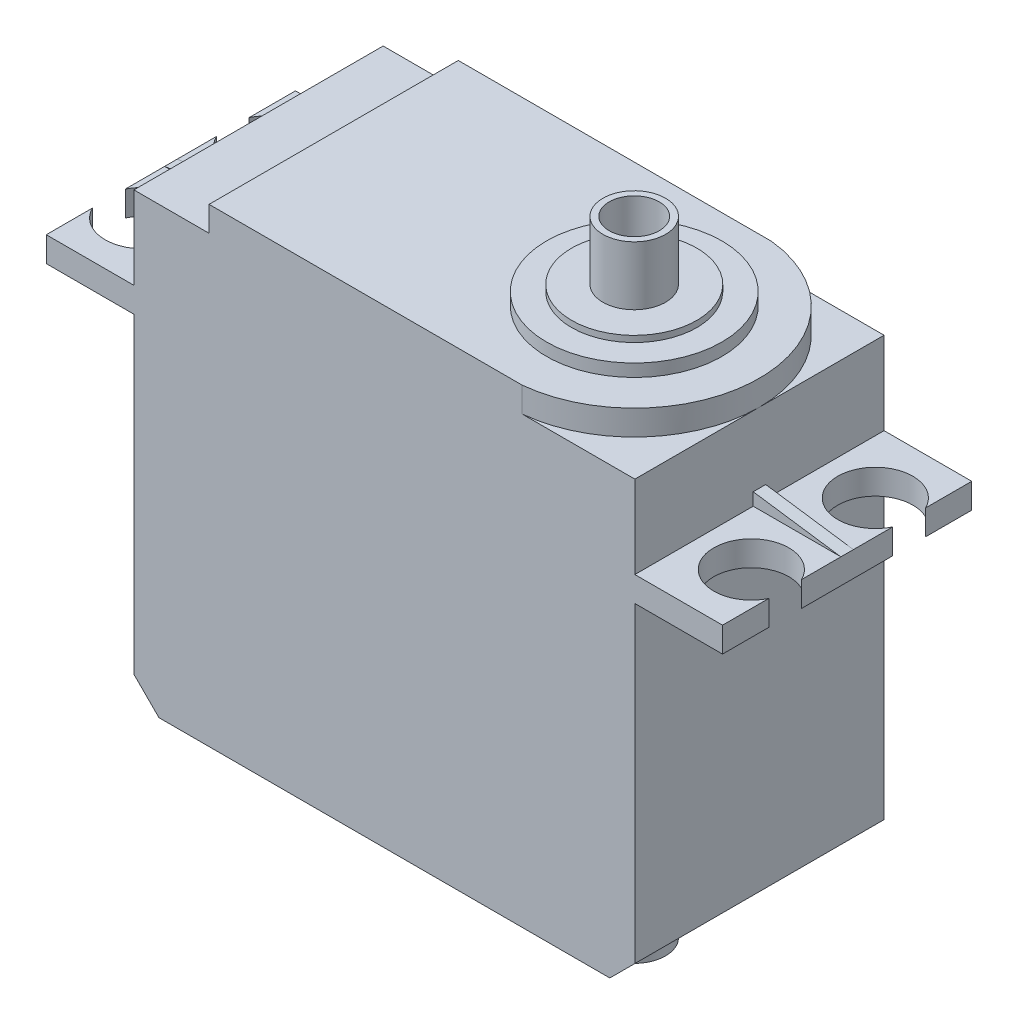
SolidWorks part; units mm, degrees
material "2024 合金"
ref_plane "前视基准面" through (0, 0, 0) normal (0, 0, 1) x (1, 0, 0)
ref_plane "上视基准面" through (0, 0, 0) normal (0, 1, 0) x (1, 0, 0)
ref_plane "右视基准面" through (0, 0, 0) normal (1, 0, 0) x (0, 0, -1)
sketch "草图2" plane through (0, 0, 0) normal (0, 0, 1) x (1, 0, 0)
  line L0 (0, 0) -> (32102.8092, 0) construction
  line L1 (0, 0) -> (0, 32102.8092) construction
  line L3 (-20, 18.75) -> (20, 18.75)
  line L4 (-20, 18.75) -> (-20, -18.75)
  line L5 (-20, -18.75) -> (20, -18.75)
  line L6 (20, 18.75) -> (20, -18.75)
  line L7 (-20, 18.75) -> (20, -18.75) construction
  line L8 (-20, -18.75) -> (20, 18.75) construction
  point P5 (0, 0)
  dimension "D1" = 37.5
  dimension "D2" = 40
extrude "凸台-拉伸1" add sketch "草图2" along normal mid plane 19.9
sketch "草图3" plane through (0, 0, 9.95) normal (0, 0, 1) x (1, 0, 0)
  line L0 (-20, 0) -> (20, 0) construction
  line L1 (-20, 18.75) -> (-20, -18.75) construction
  line L2 (20, -18.75) -> (20, 18.75) construction
  line L3 (0, 18.75) -> (0, -18.75) construction
  line L4 (20, 18.75) -> (-20, 18.75) construction
  line L5 (-20, -18.75) -> (20, -18.75) construction
  line L6 (20, 8.15) -> (27, 8.15)
  line L7 (27, 8.15) -> (27, 10.15)
  line L8 (27, 10.15) -> (20, 10.15)
  line L9 (20, 10.15) -> (20, 8.15)
  line L10 (-27, 10.15) -> (-20, 10.15)
  line L11 (-27, 8.15) -> (-27, 10.15)
  line L12 (-20, 8.15) -> (-27, 8.15)
  line L13 (-20, 8.15) -> (-20, 10.15)
  dimension "D1" = 26.9
  dimension "D2" = 2
  dimension "D3" = 7
extrude "凸台-拉伸2" add sketch "草图3" against normal blind 19.9 separate body
sketch "草图4" plane through (0, 10.15, 0) normal (0, 1, 0) x (1, 0, 0)
  line L0 (-27, 0) -> (27, 0) construction
  line L1 (-27, 9.95) -> (-27, -9.95) construction
  line L2 (27, 9.95) -> (27, -9.95) construction
  line L3 (0, 9.95) -> (0, -9.95) construction
  line L4 (20, 9.95) -> (-20, 9.95) construction
  line L5 (20, -9.95) -> (-20, -9.95) construction
  circle A0 centre (-24.3, 4.95) radius 3
  circle A2 centre (24.3, 4.95) radius 3
  circle A4 centre (24.3, -4.95) radius 3
  circle A5 centre (-24.3, -4.95) radius 3
  dimension "D1" = 6
  dimension "D2" = 24.3
  dimension "D3" = 24.3
  dimension "D6" = 4.95
extrude "切除-拉伸1" cut sketch "草图4" against normal blind 19.9
sketch "草图5" plane through (0, 10.15, 0) normal (0, 1, 0) x (1, 0, 0)
  line L0 (-27, 0) -> (-20, 0) construction
  line L1 (-27, 3.6423) -> (-27, -3.6423) construction
  line L2 (27, 3.6423) -> (27, -3.6423) construction
  line L3 (-27, 0) -> (-27, 0.5)
  line L4 (-27, 0.5) -> (-20, 0.5)
  line L5 (27, 0.5) -> (27, -0.5)
  line L6 (27, -0.5) -> (20, -0.5)
  line L7 (-27, -0.5) -> (-27, 0)
  line L8 (-20, 0.5) -> (-20, -0.5)
  line L9 (-20, -9.95) -> (-20, 9.95) construction
  line L10 (-20, 9.95) -> (-20, -9.95) construction
  line L11 (20, -0.5) -> (20, 0.5)
  line L12 (20, 9.95) -> (20, -9.95) construction
  line L13 (20, 0.5) -> (27, 0.5)
  line L14 (20, 0) -> (27, 0) construction
  line L15 (-20, -0.5) -> (-27, -0.5)
extrude "凸台-拉伸3" add sketch "草图5" along normal blind 1
sketch "草图6" plane through (0, 0, 0.5) normal (0, 0, 1) x (1, 0, 0)
  line L0 (20, 11.15) -> (27, 10.15)
  line L1 (20, 11.15) -> (27, 11.15) construction
  line L2 (20, 11.15) -> (20, 10.15) construction
  line L3 (27, 10.15) -> (27, 11.15)
  line L4 (27, 11.15) -> (20, 11.15)
  line L5 (-27, 10.15) -> (-27, 11.15)
  line L6 (-27, 11.15) -> (-20, 11.15)
  line L7 (-20, 11.15) -> (-27, 10.15)
extrude "切除-拉伸2" cut sketch "草图6" against normal through all
sketch "草图8" plane through (0, 18.75, 0) normal (0, 1, 0) x (1, 0, 0)
  line L2 (20, -9.95) -> (-20, -9.95) construction
  line L4 (20, 9.95) -> (-20, 9.95) construction
  line L6 (-24.3, 9.95) -> (-24.3, -9.95) construction
  line L7 (-20, 9.95) -> (-27, 9.95) construction
  line L8 (-20, -9.95) -> (-27, -9.95) construction
  line L16 (-13.9, -9.85) -> (-14, -9.85)
  line L18 (-13.9, 9.85) -> (-14, 9.85)
  line L19 (10, -9.95) -> (10, -9.85)
  line L20 (10, 9.95) -> (10, 9.85)
  line L21 (-20, -9.95) -> (-20, 9.95)
  line L22 (-20, 9.95) -> (-14, 9.95)
  line L23 (20, 9.95) -> (20, -9.95)
  line L24 (20, -9.95) -> (10, -9.95)
  line L25 (-14, -9.85) -> (-14, -9.95)
  line L26 (-14, 9.95) -> (-14, 9.85)
  line L27 (-14, -9.95) -> (-20, -9.95)
  line L28 (10, 9.95) -> (20, 9.95)
  line L29 (10, -9.95) -> (20, -9.95)
  line L30 (20, 9.95) -> (10, 9.95)
  line L31 (-14, -9.85) -> (-14, 9.85)
  arc A0 (10, -9.95) -> (10, 9.95) centre (10, 0) ccw
  line M20 (20, 9.95) -> (-20, 9.95)
  line M21 (-20, 9.95) -> (-20, -9.95)
  line M22 (-20, -9.95) -> (20, -9.95)
extrude "切除-拉伸6" cut sketch "草图8" against normal blind 2 contours L25 L31 L26 M20 M21 M22
sketch "草图9" plane through (0, 18.75, 0) normal (0, 1, 0) x (1, 0, 0)
  line L0 (-24.3, 9.95) -> (-24.3, -9.95) construction
  line L1 (-20, 9.95) -> (-27, 9.95) construction
  line L2 (-20, -9.95) -> (-27, -9.95) construction
  line L3 (-24.3, 0) -> (10, 0) construction
  line L4 (10, 10) -> (20, 9.95)
  line L5 (20, 9.95) -> (20, -9.95)
  line L6 (20, -9.95) -> (10, -10)
  arc A1 (10, -10) -> (10, 10) centre (10, 0) ccw
  line M5 (-14, -9.95) -> (20, -9.95)
  line M6 (20, -9.95) -> (20, 9.95)
  line M7 (20, 9.95) -> (-14, 9.95)
  dimension "D1" = 34.3
extrude "切除-拉伸7" cut sketch "草图9" against normal blind 2 contours A1 L5 M7 | A1 M5 M6
sketch "草图10" plane through (0, 18.75, 0) normal (0, 1, 0) x (1, 0, 0)
  line L0 (-24.3, 4.95) -> (-24.3, -4.95) construction
  line L1 (-24.3, 0) -> (10, 0) construction
  circle A0 centre (10, 0) radius 2
  circle A1 centre (10, 0) radius 2.5
  dimension "D2" = 4
  dimension "D3" = 5
  dimension "D1" = 34.3
extrude "凸台-拉伸4" add sketch "草图10" along normal blind 6.2
sketch "草图11" plane through (0, 18.75, 0) normal (0, 1, 0) x (1, 0, 0)
  circle A0 centre (10, 0) radius 7
  dimension "D1" = 14
extrude "凸台-拉伸5" add sketch "草图11" along normal blind 1
sketch "草图12" plane through (0, 19.75, 0) normal (0, 1, 0) x (1, 0, 0)
  circle A0 centre (10, 0) radius 5
  dimension "D1" = 10
extrude "凸台-拉伸6" add sketch "草图12" along normal blind 0.5
sketch "草图13" plane through (0, -18.75, 0) normal (0, -1, 0) x (1, 0, 0)
  circle A0 centre (10, 0) radius 2
  circle A1 centre (10, 0) radius 2.5
extrude "凸台-拉伸7" add sketch "草图13" along normal blind 6.2
chamfer "倒角1" distance 2 angle 45 2 edges at (-20, -18.75, 0) (20, -18.75, 0)
